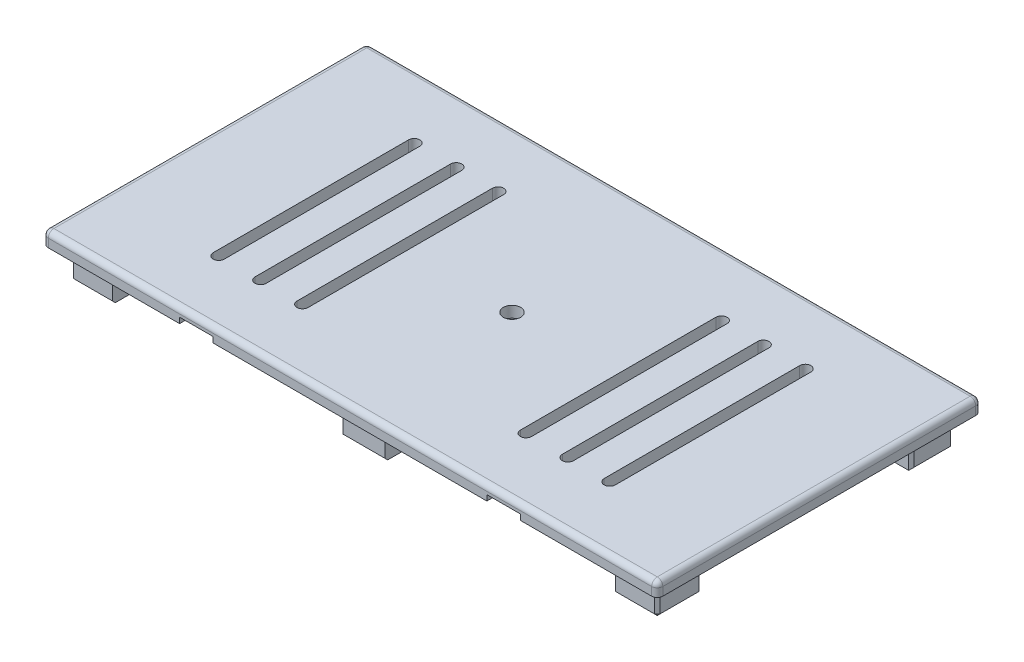
SolidWorks part; units mm, degrees
ref_plane "Front Plane" through (0, 0, 0) normal (0, 0, 1) x (1, 0, 0)
ref_plane "Top Plane" through (0, 0, 0) normal (0, 1, 0) x (1, 0, 0)
ref_plane "Right Plane" through (0, 0, 0) normal (1, 0, 0) x (0, 0, -1)
sketch "Sketch1" plane through (0, 0, 0) normal (0, 1, 0) x (1, 0, 0)
  line L1 (0, 0) -> (110, 0)
  line L2 (0, 0) -> (0, 58)
  line L3 (0, 58) -> (110, 58)
  line L4 (110, 0) -> (110, 58)
  dimension "D1" = 110
  dimension "D2" = 58
extrude "Boss-Extrude1" add sketch "Sketch1" along normal blind 2.5
sketch "Sketch2" plane through (0, 0, 0) normal (0, -1, 0) x (1, 0, 0)
  line L0 (0, -58) -> (0, 0) construction
  line L1 (2.5, -55.5) -> (107.5, -55.5)
  line L2 (2.5, -55.5) -> (2.5, -2.5)
  line L3 (2.5, -2.5) -> (107.5, -2.5)
  line L4 (107.5, -55.5) -> (107.5, -2.5)
  line L5 (0, 0) -> (110, 0) construction
  line L6 (110, 0) -> (110, -58) construction
  line L7 (110, -58) -> (0, -58) construction
  dimension "D1" = 2.5
  dimension "D2" = 2.5
  dimension "D3" = 2.5
  dimension "D4" = 2.5
  dimension "D5" = 53
  dimension "D6" = 105
extrude "Boss-Extrude2" add sketch "Sketch2" along normal blind 1.5
sketch "Sketch3" plane through (0, -1.5, 0) normal (0, -1, 0) x (1, 0, 0)
  line L0 (55, -5.5) -> (55, -55.5) construction
  line L1 (2.5, -55.5) -> (107.5, -55.5) construction
  line L2 (2.5, -55.5) -> (107.5, -55.5) construction
  line L3 (107.5, -29) -> (2.5, -29) construction
  line L4 (107.5, -55.5) -> (107.5, -2.5) construction
  line L5 (2.5, -2.5) -> (2.5, -55.5) construction
  line L6 (58.75, -2.5) -> (58.75, -5.5)
  line L7 (2.5, -2.5) -> (10, -2.5)
  line L8 (2.5, -2.5) -> (2.5, -10)
  line L9 (2.5, -10) -> (5.5, -10)
  line L10 (10, -2.5) -> (10, -5.5)
  line L13 (10, -5.5) -> (5.5, -5.5)
  line L14 (5.5, -10) -> (5.5, -5.5)
  line L15 (58.75, -2.5) -> (51.25, -2.5)
  line L17 (58.75, -5.5) -> (51.25, -5.5)
  line L18 (51.25, -2.5) -> (51.25, -5.5)
  line L19 (107.5, -2.5) -> (107.5, -10)
  line L20 (107.5, -10) -> (104.5, -10)
  line L21 (104.5, -10) -> (104.5, -5.5)
  line L22 (100, -5.5) -> (104.5, -5.5)
  line L23 (100, -2.5) -> (100, -5.5)
  line L24 (107.5, -2.5) -> (100, -2.5)
  line L25 (107.5, -55.5) -> (100, -55.5)
  line L26 (100, -55.5) -> (100, -52.5)
  line L27 (100, -52.5) -> (104.5, -52.5)
  line L28 (104.5, -48) -> (104.5, -52.5)
  line L29 (107.5, -48) -> (104.5, -48)
  line L30 (107.5, -55.5) -> (107.5, -48)
  line L31 (58.75, -55.5) -> (58.75, -52.5)
  line L32 (58.75, -55.5) -> (51.25, -55.5)
  line L33 (51.25, -55.5) -> (51.25, -52.5)
  line L34 (58.75, -52.5) -> (51.25, -52.5)
  line L35 (2.5, -55.5) -> (2.5, -48)
  line L36 (2.5, -48) -> (5.5, -48)
  line L37 (5.5, -48) -> (5.5, -52.5)
  line L38 (10, -52.5) -> (5.5, -52.5)
  line L39 (10, -55.5) -> (10, -52.5)
  line L40 (2.5, -55.5) -> (10, -55.5)
  dimension "D1" = 7.5
  dimension "D2" = 7.5
  dimension "D3" = 3
  dimension "D4" = 3
  dimension "D5" = 7.5
  dimension "D6" = 3
extrude "Boss-Extrude3" add sketch "Sketch3" along normal blind 4
fillet "Fillet1" radius 1 4 edges at (5.5, -3.5, -52.5) (104.5, -3.5, -52.5) (104.5, -3.5, -5.5) (5.5, -3.5, -5.5)
sketch "Sketch4" plane through (0, 0, 0) normal (0, -1, 0) x (1, 0, 0)
  line L0 (55, 0) -> (55, -58) construction
  line L1 (0, 0) -> (110, 0) construction
  line L2 (110, -58) -> (0, -58) construction
  line L3 (0, -29) -> (55, -29) construction
  line L4 (0, -58) -> (0, 0) construction
  line L6 (27.5, -29) -> (27.5, -2.5) construction
  line L7 (107.5, -2.5) -> (2.5, -2.5) construction
  line L8 (30.5, 0) -> (24.5, 0)
  line L10 (30.5, -2.5) -> (24.5, -2.5)
  line L11 (24.5, 0) -> (24.5, -2.5)
  line L12 (30.5, 0) -> (30.5, -2.5)
  line L13 (79.5, 0) -> (79.5, -2.5)
  line L14 (79.5, 0) -> (85.5, 0)
  line L15 (85.5, 0) -> (85.5, -2.5)
  line L16 (79.5, -2.5) -> (85.5, -2.5)
  line L17 (79.5, -58) -> (85.5, -58)
  line L18 (85.5, -58) -> (85.5, -55.5)
  line L19 (79.5, -55.5) -> (85.5, -55.5)
  line L20 (79.5, -58) -> (79.5, -55.5)
  line L21 (30.5, -58) -> (30.5, -55.5)
  line L22 (30.5, -58) -> (24.5, -58)
  line L23 (24.5, -58) -> (24.5, -55.5)
  line L24 (30.5, -55.5) -> (24.5, -55.5)
extrude "Cut-Extrude1" cut sketch "Sketch4" against normal blind 1
fillet "Fillet2" radius 1 4 edges at (0, 1.25, -58) (0, 1.25, 0) (110, 1.25, -58) (110, 1.25, 0)
chamfer "Chamfer1" distance 0.5 angle 45 18 edges at (55, -5.5, -55.5) (2.5, -3.5, -48) (2.5, -2.75, -55.5) (10, -3.5, -55.5) (107.5, -3.5, -48) (100, -3.5, -55.5) (107.5, -2.75, -55.5) (107.5, -2.75, -2.5) (107.5, -5.5, -6.25) (103.75, -5.5, -2.5) (55, -5.5, -2.5) (2.5, -5.5, -6.25) (6.25, -5.5, -2.5) (2.5, -2.75, -2.5) (2.5, -5.5, -51.75) (6.25, -5.5, -55.5) (103.75, -5.5, -55.5) (107.5, -5.5, -51.75)
sketch "Sketch5" plane through (0, 2.5, 0) normal (0, 1, 0) x (1, 0, 0)
  line L0 (0, 29) -> (55, 29) construction
  line L1 (0, 57) -> (0, 1) construction
  line L3 (55, 58) -> (55, 0) construction
  line L4 (109, 58) -> (1, 58) construction
  line L5 (1, 0) -> (109, 0) construction
  line L6 (27.5, 29) -> (27.5, 46.5) construction
  line L11 (27.5, 29) -> (27.5, 11.5) construction
  line L14 (27.5, 46.5) -> (27.5, 11.5) construction
  line L17 (28.5, 46.5) -> (28.5, 11.5)
  line L20 (26.5, 46.5) -> (26.5, 11.5)
  line L23 (34, 46.5) -> (34, 11.5)
  line L26 (36, 46.5) -> (36, 11.5)
  line L27 (35, 46.5) -> (35, 11.5) construction
  line L28 (20, 46.5) -> (20, 11.5) construction
  line L29 (21, 46.5) -> (21, 11.5)
  line L30 (19, 46.5) -> (19, 11.5)
  line L31 (90, 46.5) -> (90, 11.5) construction
  line L32 (89, 46.5) -> (89, 11.5)
  line L33 (91, 46.5) -> (91, 11.5)
  line L34 (75, 46.5) -> (75, 11.5) construction
  line L35 (74, 46.5) -> (74, 11.5)
  line L36 (76, 46.5) -> (76, 11.5)
  line L37 (82.5, 46.5) -> (82.5, 11.5) construction
  line L38 (81.5, 46.5) -> (81.5, 11.5)
  line L39 (83.5, 46.5) -> (83.5, 11.5)
  arc A14 (28.5, 46.5) -> (26.5, 46.5) centre (27.5, 46.5) ccw
  arc A15 (26.5, 11.5) -> (28.5, 11.5) centre (27.5, 11.5) ccw
  arc A16 (36, 46.5) -> (34, 46.5) centre (35, 46.5) ccw
  arc A17 (34, 11.5) -> (36, 11.5) centre (35, 11.5) ccw
  arc A18 (21, 46.5) -> (19, 46.5) centre (20, 46.5) ccw
  arc A19 (19, 11.5) -> (21, 11.5) centre (20, 11.5) ccw
  arc A20 (89, 46.5) -> (91, 46.5) centre (90, 46.5) cw
  arc A21 (91, 11.5) -> (89, 11.5) centre (90, 11.5) cw
  arc A22 (74, 46.5) -> (76, 46.5) centre (75, 46.5) cw
  arc A23 (76, 11.5) -> (74, 11.5) centre (75, 11.5) cw
  arc A24 (81.5, 46.5) -> (83.5, 46.5) centre (82.5, 46.5) cw
  arc A25 (83.5, 11.5) -> (81.5, 11.5) centre (82.5, 11.5) cw
  point P5 (27.5, 29)
  point P21 (35, 29)
  point P27 (20, 29)
  point P34 (90, 29)
  point P41 (75, 29)
  point P48 (82.5, 29)
  dimension "D3" = 1
  dimension "D1" = 17.5
  dimension "D2" = 17.5
  dimension "D4" = 2
  dimension "D5" = 2
extrude "Cut-Extrude2" cut sketch "Sketch5" against normal through all
fillet "Fillet3" radius 1 8 edges at (0.2929, 2.5, -0.2929) (0, 2.5, -29) (0.2929, 2.5, -57.7071) (55, 2.5, -58) (109.7071, 2.5, -57.7071) (110, 2.5, -29) (109.7071, 2.5, -0.2929) (55, 2.5, 0)
sketch "Sketch6" plane through (0, 2.5, 0) normal (0, 1, 0) x (1, 0, 0)
  line L0 (55, 58) -> (55, 0) construction
  line L1 (1, 58) -> (109, 58) construction
  line L2 (109, 0) -> (1, 0) construction
  circle A0 centre (55, 29) radius 1.55
  dimension "D1" = 3.1
extrude "Cut-Extrude3" cut sketch "Sketch6" against normal through all
sketch "Sketch7" plane through (0, -1.5, 0) normal (0, -1, 0) x (1, 0, 0)
  circle A0 centre (55, -29) radius 2.05
  dimension "D1" = 4.1
extrude "Cut-Extrude4" cut sketch "Sketch7" against normal blind 2
